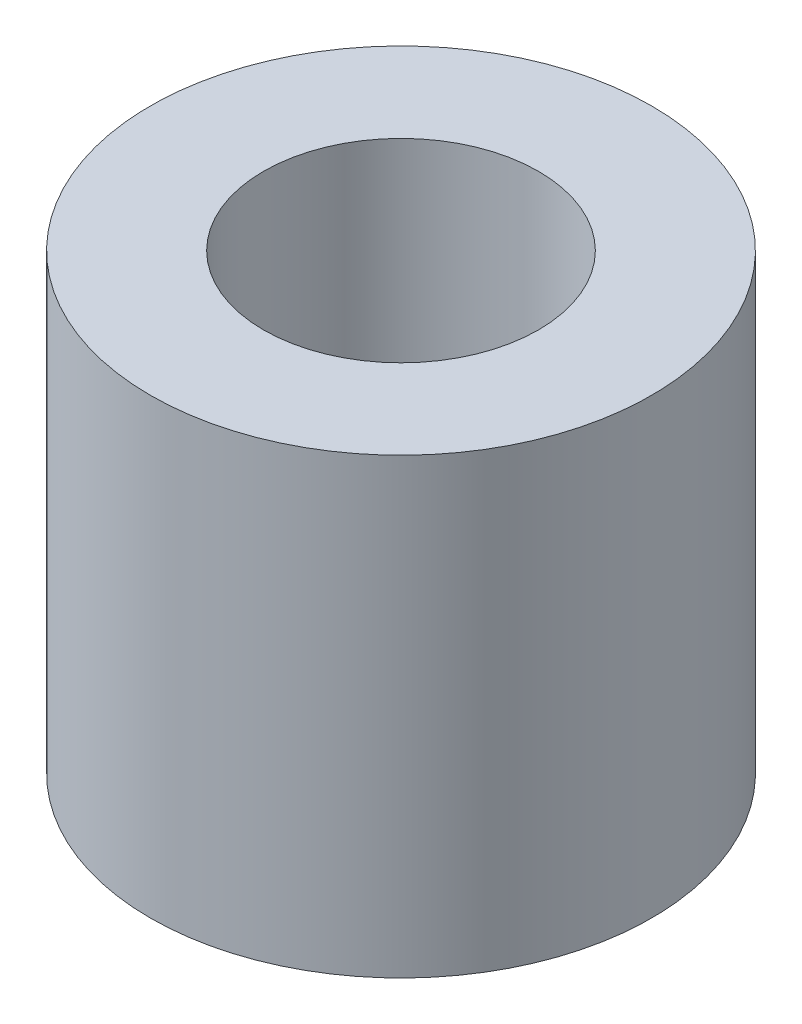
SolidWorks part; units mm, degrees
ref_plane "Front" through (0, 0, 0) normal (0, 0, 1) x (1, 0, 0)
ref_plane "Top" through (0, 0, 0) normal (0, 1, 0) x (1, 0, 0)
ref_plane "Right" through (0, 0, 0) normal (1, 0, 0) x (0, 0, -1)
sketch "Sketch1" plane through (0, 0, 0) normal (0, 1, 0) x (1, 0, 0)
  circle A0 centre (0, 0) radius 2.125
  circle A1 centre (0, 0) radius 3.875
  dimension "D1" = 4.25
  dimension "D2" = 7.75
extrude "Boss-Extrude1" add sketch "Sketch1" along normal blind 7
